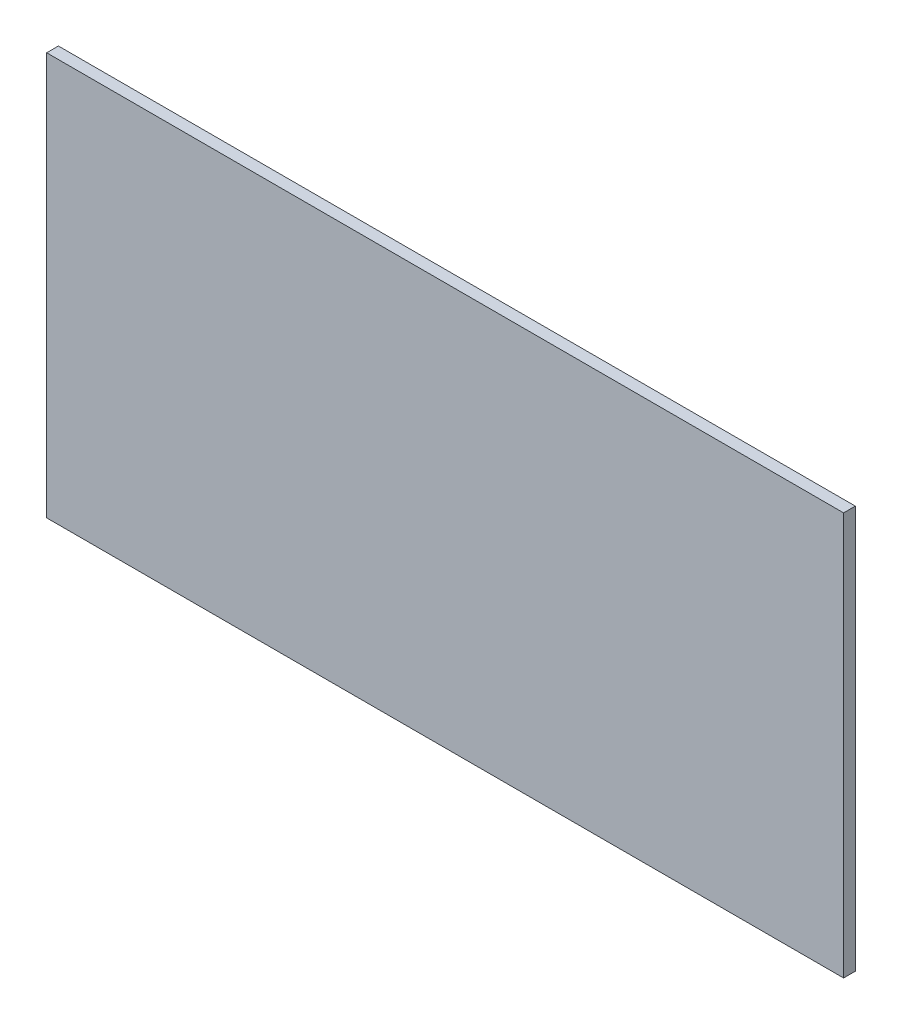
SolidWorks part; units mm, degrees
ref_plane "Front Plane" through (0, 0, 0) normal (0, 0, 1) x (1, 0, 0)
ref_plane "Top Plane" through (0, 0, 0) normal (0, 1, 0) x (1, 0, 0)
ref_plane "Right Plane" through (0, 0, 0) normal (1, 0, 0) x (0, 0, -1)
sketch "Sketch1" plane through (0, 0, 0) normal (0, 0, 1) x (1, 0, 0)
  line L1 (-54.3901, 27.4928) -> (54.3901, 27.4928)
  line L2 (-54.3901, 27.4928) -> (-54.3901, -27.4928)
  line L3 (-54.3901, -27.4928) -> (54.3901, -27.4928)
  line L4 (54.3901, 27.4928) -> (54.3901, -27.4928)
  line L5 (-54.3901, 27.4928) -> (54.3901, -27.4928) construction
  line L6 (-54.3901, -27.4928) -> (54.3901, 27.4928) construction
  point P0 (0, 0)
extrude "Boss-Extrude1" add sketch "Sketch1" along normal blind 1.6
